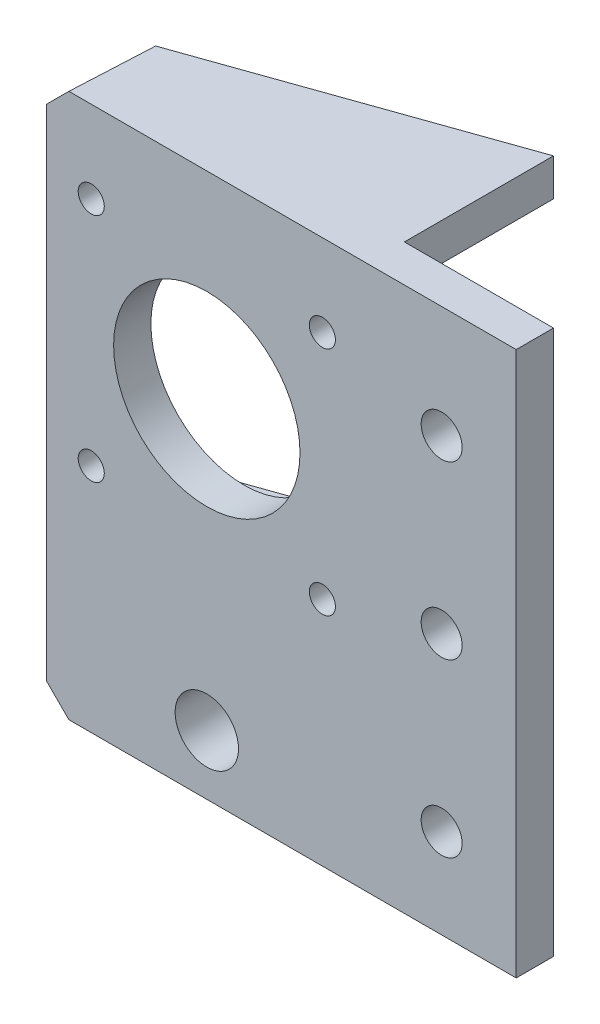
SolidWorks part; units mm, degrees
ref_plane "前视基准面" through (0, 0, 0) normal (0, 0, 1) x (1, 0, 0)
ref_plane "上视基准面" through (0, 0, 0) normal (0, 1, 0) x (1, 0, 0)
ref_plane "右视基准面" through (0, 0, 0) normal (1, 0, 0) x (0, 0, -1)
sketch "草图2" plane through (0, 0, 0) normal (0, 0, 1) x (1, 0, 0)
  line L0 (23.028, -31.0315) -> (23.028, 11.9685) construction
  line L1 (-19.972, 11.9685) -> (43.028, 11.9685)
  line L2 (-19.972, 11.9685) -> (-19.972, -31.0315)
  line L3 (-19.972, -31.0315) -> (43.028, -31.0315)
  line L4 (43.028, 11.9685) -> (43.028, -31.0315)
  line L5 (-19.972, 11.9685) -> (43.028, -31.0315) construction
  line L6 (-19.972, -31.0315) -> (43.028, 11.9685) construction
  line L7 (23.028, -9.5315) -> (-19.972, -9.5315) construction
  line L8 (33.028, -31.0315) -> (33.028, 11.9685) construction
  line L9 (-13.972, 5.9685) -> (17.028, 5.9685) construction
  line L10 (-13.972, 5.9685) -> (-13.972, -25.0315) construction
  line L11 (-13.972, -25.0315) -> (17.028, -25.0315) construction
  line L12 (17.028, 5.9685) -> (17.028, -25.0315) construction
  line L13 (1.528, -25.0315) -> (1.528, 5.9685) construction
  line L14 (-13.972, -9.5315) -> (17.028, -9.5315) construction
  circle A0 centre (-13.972, 5.9685) radius 1.75
  circle A1 centre (17.028, 5.9685) radius 1.75
  circle A2 centre (17.028, -25.0315) radius 1.75
  circle A3 centre (-13.972, -25.0315) radius 1.75
  circle A4 centre (1.528, -9.5315) radius 12.5
  circle A5 centre (33.028, 1.9685) radius 2.75
  circle A6 centre (33.028, -21.0315) radius 2.75
  point P4 (11.528, -9.5315)
  point P9 (1.528, -9.5315)
  dimension "D6" = 25
  dimension "D7" = 3.5
  dimension "D8" = 5.5
  dimension "D9" = 5.5
  dimension "D1" = 63
  dimension "D2" = 43
  dimension "D3" = 43
  dimension "D4" = 31
  dimension "D5" = 31
  dimension "D10" = 10
  dimension "D11" = 10
  dimension "D12" = 10
extrude "凸台-拉伸1" add sketch "草图2" along normal blind 5
sketch "草图3" plane through (0, -31.0315, 0) normal (0, -1, 0) x (1, 0, 0)
  line L4 (-19.972, 0) -> (43.028, 0)
  line L5 (43.028, 0) -> (43.028, 5)
  line L6 (43.028, 5) -> (-19.972, 5)
  line L7 (-19.972, 5) -> (-19.972, 0)
  line L8 (-19.972, 0) -> (43.028, 0)
  line L9 (43.028, 0) -> (43.028, 5)
  line L10 (43.028, 5) -> (-19.972, 5)
  line L11 (-19.972, 5) -> (-19.972, 0)
  dimension "D1" = 0
extrude "凸台-拉伸2" add sketch "草图3" along normal blind 25
sketch "草图4" plane through (0, 0, 5) normal (0, 0, 1) x (1, 0, 0)
  line L0 (1.528, -9.5315) -> (1.528, -56.0315) construction
  line L1 (43.028, -56.0315) -> (-19.972, -56.0315) construction
  circle A0 centre (1.528, -48.0315) radius 4.25
  dimension "D1" = 8.5
  dimension "D2" = 8
extrude "切除-拉伸2" cut sketch "草图4" against normal blind 25
sketch "草图5" plane through (0, 0, 0) normal (0, 0, -1) x (-1, 0, 0)
  circle A0 centre (-1.528, -48.0315) radius 7.75
  circle A1 centre (-1.528, -48.0315) radius 4.25
  dimension "D2" = 3.5
extrude "凸台-拉伸3" add sketch "草图5" along normal blind 10
sketch "草图7" plane through (0, 11.9685, 0) normal (0, 1, 0) x (1, 0, 0)
  line L0 (-19.972, -5) -> (-19.472, 5)
  line L1 (-19.472, 0) -> (-19.472, 40) construction
  line L2 (-19.472, 5) -> (23.028, 20)
  line L3 (23.028, 20) -> (23.028, -5)
  line L4 (43.028, -5) -> (-19.972, -5) construction
  line L5 (23.028, -5) -> (-19.972, -5)
  line L6 (43.028, -5) -> (43.028, 0) construction
  dimension "D1" = 10
  dimension "D2" = 25
  dimension "D3" = 20
extrude "凸台-拉伸4" add sketch "草图7" along normal blind 5
ref_plane "基准面1" through (0, -31.0315, 0) normal (0, -1, 0) x (-1, 0, 0)
sketch "草图8" plane through (0, -31.0315, 0) normal (0, -1, 0) x (-1, 0, 0)
  line L4 (-23.028, 20) -> (-23.028, 0)
  line L5 (-23.028, 0) -> (19.722, 0)
  line L6 (19.722, 0) -> (19.472, 5)
  line L7 (19.472, 5) -> (-23.028, 20)
  line L8 (-23.028, 20) -> (-23.028, 0)
  line L9 (-23.028, 0) -> (19.722, 0)
  line L10 (19.722, 0) -> (19.472, 5)
  line L11 (19.472, 5) -> (-23.028, 20)
  dimension "D1" = 0
extrude "凸台-拉伸5" add sketch "草图8" along normal blind 5
sketch "草图10" plane through (0, 0, 5) normal (0, 0, 1) x (1, 0, 0)
  line L0 (33.028, -21.0315) -> (33.028, -56.0315) construction
  line L1 (43.028, -56.0315) -> (-19.972, -56.0315) construction
  circle A0 centre (33.028, -44.0315) radius 2.75
  dimension "D2" = 5.5
  dimension "D1" = 12
extrude "切除-拉伸3" cut sketch "草图10" against normal through all
sketch "草图11" plane through (0, 11.9685, 0) normal (0, 1, 0) x (1, 0, 0)
  line L4 (23.028, 0) -> (23.028, -5)
  line L5 (23.028, -5) -> (43.028, -5)
  line L6 (43.028, -5) -> (43.028, 0)
  line L7 (43.028, 0) -> (23.028, 0)
  line L8 (23.028, 0) -> (23.028, -5)
  line L9 (23.028, -5) -> (43.028, -5)
  line L10 (43.028, -5) -> (43.028, 0)
  line L11 (43.028, 0) -> (23.028, 0)
  dimension "D1" = 0
extrude "凸台-拉伸6" add sketch "草图11" along normal blind 5
chamfer "倒角1" distance 3 angle 45 2 edges at (-19.722, 16.9685, 0) (-19.972, -56.0315, 2.5)
